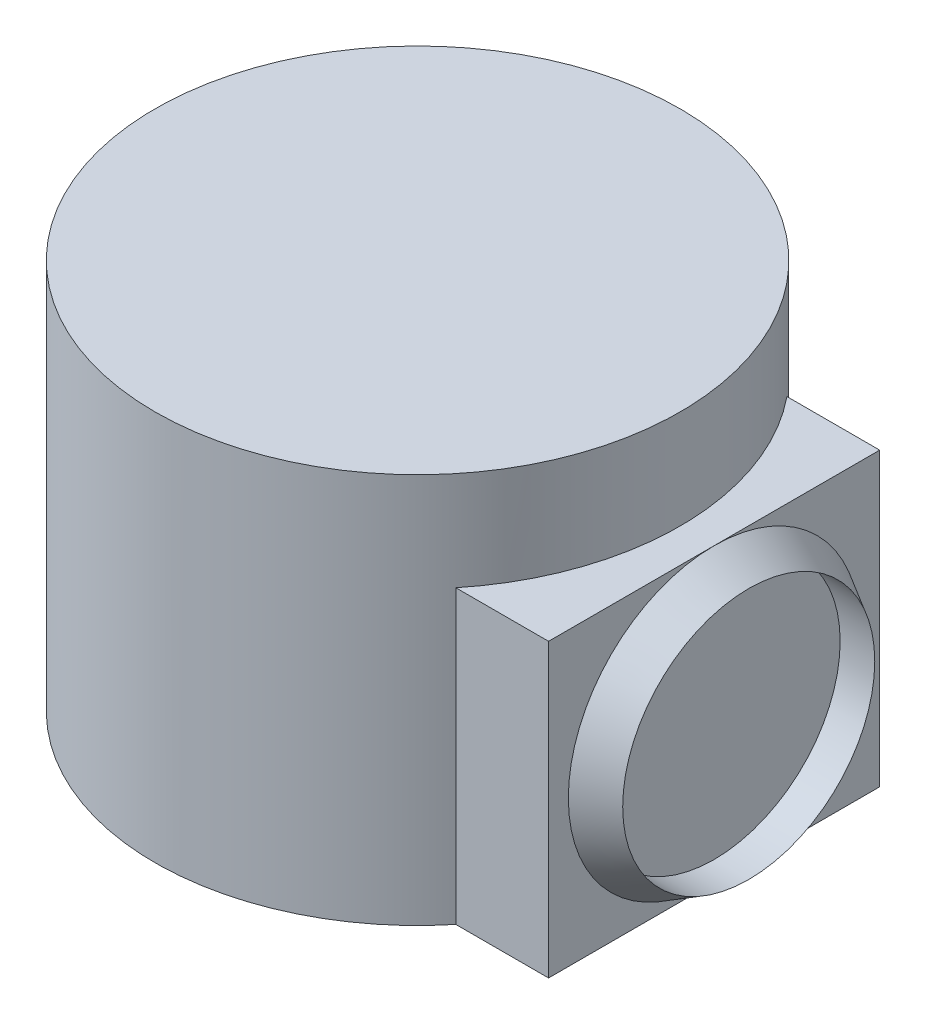
SolidWorks part; units mm, degrees
ref_plane "Front Plane" through (0, 0, 0) normal (0, 0, 1) x (1, 0, 0)
ref_plane "Top Plane" through (0, 0, 0) normal (0, 1, 0) x (1, 0, 0)
ref_plane "Right Plane" through (0, 0, 0) normal (1, 0, 0) x (0, 0, -1)
sketch "Sketch1" plane through (0, 0, 0) normal (0, 1, 0) x (1, 0, 0)
  circle A0 centre (0, 0) radius 132.8125
extrude "Boss-Extrude1" add sketch "Sketch1" along normal blind 147.5
sketch "Sketch2" plane through (0, 0, 0) normal (1, 0, 0) x (0, 0, -1)
  line L1 (132.8125, 147.5) -> (-132.8125, 147.5) construction
  line L3 (-83.75, 147.5) -> (-83.75, 0)
  line L4 (-132.8125, 0) -> (132.8125, 0) construction
  line L5 (-83.75, 0) -> (83.75, 0)
  line L6 (83.75, 0) -> (83.75, 147.5)
  line L7 (83.75, 147.5) -> (-83.75, 147.5)
extrude "Boss-Extrude2" add sketch "Sketch2" along normal blind 150
sketch "Sketch3" plane through (150, 0, 0) normal (1, 0, 0) x (0, 0, -1)
  line L0 (0, 0) -> (0, 20) construction
  line L1 (-83.75, 0) -> (83.75, 0) construction
sketch "Sketch4" plane through (0, 0, 0) normal (0, 0, 1) x (1, 0, 0)
  line L0 (150, 0) -> (150, 10)
  line L1 (150, 0) -> (150, 20) construction
  line L2 (150, 0) -> (150, 147.5) construction
  line L3 (150, 10) -> (167.5, 10)
  line L4 (167.5, 10) -> (150, 0)
  line L5 (150, 0) -> (150, 73.75) construction
  line L6 (150, 73.75) -> (215.633, 73.75) construction
revolve "Revolve1" add sketch "Sketch4" angle 360 about L6
sketch "Sketch5" plane through (0, 147.5, 0) normal (0, 1, 0) x (1, 0, 0)
  circle A0 centre (0, 0) radius 132.8125
extrude "Boss-Extrude3" add sketch "Sketch5" along normal blind 50
